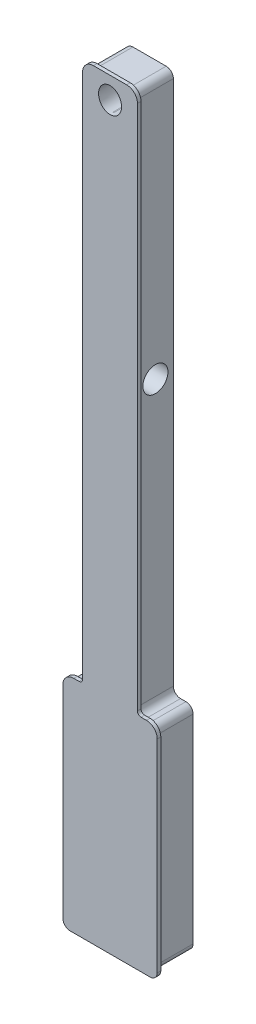
SolidWorks part; units mm, degrees
ref_plane "Plan de face" through (0, 0, 0) normal (0, 0, 1) x (1, 0, 0)
ref_plane "Plan de dessus" through (0, 0, 0) normal (0, 1, 0) x (1, 0, 0)
ref_plane "Plan de droite" through (0, 0, 0) normal (1, 0, 0) x (0, 0, -1)
sketch "Esquisse1" plane through (0, 0, 0) normal (0, 0, 1) x (1, 0, 0)
  line L5 (-28.748, 301.5704) -> (-28.748, 373.5704)
  line L12 (-34.248, 163.5704) -> (-9.978, 163.5704)
  line L21 (-34.248, 223.0046) -> (-28.748, 223.0046)
  line L22 (-34.248, 163.5704) -> (-34.248, 223.0046)
  line L28 (-15.478, 301.5704) -> (-15.478, 223.5671)
  line L29 (-15.478, 223.5671) -> (-15.478, 223.0046)
  line L30 (-15.478, 223.0046) -> (-9.978, 223.0046)
  line L31 (-9.978, 223.0046) -> (-9.978, 163.5704)
  line L36 (-28.748, 223.0046) -> (-28.748, 301.5704)
  line L38 (-28.748, 373.5704) -> (-15.478, 373.5704)
  line L39 (-15.478, 373.5704) -> (-15.478, 301.5704)
  dimension "D2" = 5.5
  dimension "D3" = 5.5
  dimension "D11" = 24.27
extrude "Boss.-Extru.1" add sketch "Esquisse1" along normal blind 10 contours L31 L12 L22 L21 L36 L5 L38 L39 L28 L29 L30
sketch "Esquisse2" plane through (0, 0, 10) normal (0, 0, 1) x (1, 0, 0)
  line L0 (-22.113, 373.5704) -> (-22.113, 368.5704) construction
  line L1 (-28.748, 373.5704) -> (-15.478, 373.5704) construction
  line L2 (-28.748, 223.0046) -> (-28.748, 373.5704) construction
  ellipse E0 centre (-22.113, 368.5704) end of major axis (-22.113, 372.0704) minor radius 3
  dimension "D1" = 6.635
  dimension "D2" = 5
extrude "Enlèv. mat.-Extru.1" cut sketch "Esquisse2" against normal blind 10
sketch "Esquisse3" plane through (0, 0, 10) normal (0, 0, 1) x (1, 0, 0)
  circle A0 centre (-22.113, 368.5704) radius 3.2
extrude "Enlèv. mat.-Extru.2" cut sketch "Esquisse3" against normal blind 10
sketch "Esquisse4" plane through (-15.478, 0, 0) normal (1, 0, 0) x (0, 0, -1)
  line L0 (-5, 373.5704) -> (-5, 301.5704) construction
  line L1 (-10, 373.5704) -> (0, 373.5704) construction
  circle A0 centre (-5, 301.5704) radius 3.5
extrude "Enlèv. mat.-Extru.3" cut sketch "Esquisse4" against normal blind 30 contours A0
sketch "Esquisse5" plane through (0, 0, 10) normal (0, 0, 1) x (1, 0, 0)
  line L0 (-9.978, 223.0046) -> (-9.978, 163.5704) construction
  line L1 (-35.248, 374.5704) -> (-8.978, 374.5704)
  line L2 (-35.248, 374.5704) -> (-35.248, 162.5704)
  line L3 (-35.248, 162.5704) -> (-8.978, 162.5704)
  line L4 (-8.978, 374.5704) -> (-8.978, 162.5704)
  line L5 (-34.248, 163.5704) -> (-34.248, 223.0046) construction
  line L6 (-34.248, 163.5704) -> (-9.978, 163.5704) construction
  line L7 (-28.748, 373.5704) -> (-15.478, 373.5704) construction
  dimension "D1" = 1
  dimension "D2" = 1
  dimension "D3" = 1
  dimension "D4" = 1
extrude "Boss.-Extru.2" add sketch "Esquisse5" along normal blind 1 contours L2 L3 L4 L1
fillet "Congé1" radius 2 8 edges at (-15.478, 223.0046, 5) (-28.748, 223.0046, 5) (-9.978, 163.5704, 5) (-34.248, 163.5704, 5) (-28.748, 373.5704, 5) (-34.248, 223.0046, 5) (-9.978, 223.0046, 5) (-15.478, 373.5704, 5)
sketch "Esquisse6" plane through (0, 0, 10) normal (0, 0, -1) x (-1, 0, 0)
  line L0 (10.5638, 222.4188) -> (10.6442, 223.1259) construction
  line L1 (9.978, 221.0046) -> (8.978, 221.0046) construction
  line L3 (11.978, 223.0046) -> (11.978, 224.0046) construction
  line L4 (15.478, 225.0046) -> (14.478, 225.0046) construction
  line L5 (14.8922, 223.5904) -> (14.6071, 223.8732) construction
  line L6 (22.113, 374.5704) -> (22.113, 127.1098) construction
  line L7 (35.248, 374.5704) -> (8.978, 374.5704) construction
  line L8 (28.748, 225.0046) -> (29.748, 225.0046) construction
  line L9 (29.3338, 223.5904) -> (29.6188, 223.8732) construction
  line L10 (32.248, 223.0046) -> (32.248, 224.0046) construction
  line L11 (33.6622, 222.4188) -> (33.5818, 223.1259) construction
  line L12 (34.248, 221.0046) -> (35.248, 221.0046) construction
  line L13 (13.478, 223.0046) -> (13.478, 224.0046) construction
  line L14 (11.978, 224.0046) -> (13.478, 224.0046)
  line L15 (32.248, 224.0046) -> (30.748, 224.0046)
  line L16 (15.478, 371.5704) -> (14.478, 371.5704) construction
  line L17 (16.0638, 372.9847) -> (15.3098, 373.6441) construction
  line L18 (17.478, 373.5704) -> (17.478, 374.5704) construction
  line L20 (14.478, 371.5704) -> (14.478, 225.0046)
  line L23 (17.478, 374.5704) -> (17.478, 374.9841)
  line L24 (35.248, 221.0046) -> (36.748, 374.5705)
  line L25 (32.248, 224.0046) -> (30.748, 224.0046)
  line L26 (29.748, 371.5704) -> (29.748, 225.0046)
  line L27 (9.978, 221.0046) -> (9.978, 165.5704) construction
  line L29 (17.478, 374.9841) -> (8.9656, 374.9841)
  line L30 (8.9656, 374.9841) -> (8.9656, 221.0046)
  line L31 (9.978, 165.5704) -> (10.3655, 165.5704) construction
  line L32 (10.5638, 164.1562) -> (11.0684, 163.8734) construction
  line L33 (11.978, 163.5704) -> (11.978, 163.1704) construction
  line L35 (32.248, 163.5704) -> (11.978, 163.5704) construction
  line L43 (8.9656, 221.0046) -> (8.978, 221.0046)
  line L44 (32.248, 224.0046) -> (30.748, 224.0046)
  line L45 (29.748, 371.5704) -> (29.748, 225.0046)
  line L46 (33.6622, 222.4188) -> (34.3693, 223.1259) construction
  line L47 (29.3338, 223.5904) -> (30.0409, 224.2975) construction
  line L48 (26.748, 374.5704) -> (36.748, 374.5705)
  arc A0 (11.978, 223.0046) -> (9.978, 221.0046) centre (11.978, 221.0046) ccw construction
  arc A1 (11.978, 224.0046) -> (8.978, 221.0046) centre (11.978, 221.0046) ccw
  arc A2 (13.478, 223.0046) -> (15.478, 225.0046) centre (13.478, 225.0046) ccw construction
  arc A4 (13.478, 224.0046) -> (14.478, 225.0046) centre (13.478, 225.0046) ccw
  arc A5 (30.748, 224.0046) -> (29.748, 225.0046) centre (30.748, 225.0046) cw
  arc A7 (17.478, 373.5704) -> (15.478, 371.5704) centre (17.478, 371.5704) ccw construction
  arc A10 (30.748, 224.0046) -> (29.748, 225.0046) centre (30.748, 225.0046) cw
  arc A11 (29.748, 371.5704) -> (26.748, 374.5704) centre (26.6739, 371.4963) ccw
  arc A12 (14.478, 371.5704) -> (17.478, 374.5704) centre (17.478, 371.5704) cw
  arc A13 (9.978, 165.5704) -> (11.978, 163.5704) centre (11.978, 165.5704) ccw construction
  arc A16 (32.248, 224.0046) -> (35.248, 221.0046) centre (32.248, 221.0046) cw
  arc A17 (30.748, 224.0046) -> (29.748, 225.0046) centre (30.748, 225.0046) cw
  arc A18 (29.748, 371.5704) -> (26.748, 374.5704) centre (26.748, 371.5704) ccw
  dimension "D1" = 1
  dimension "D2" = 1
extrude "Enlèv. mat.-Extru.4" cut sketch "Esquisse6" against normal blind 1
fillet "Congé4" radius 2 2 edges at (-35.248, 162.5704, 10.5) (-8.978, 162.5704, 10.5)
sketch "Esquisse10" plane through (0, 0, 0) normal (0, 0, -1) x (-1, 0, 0)
  circle A0 centre (22.113, 368.5704) radius 3.2
extrude "Enlèv. mat.-Extru.9" cut sketch "Esquisse10" against normal blind 15 contours A0
sketch "Esquisse11" plane through (0, 0, 0) normal (0, 0, -1) x (-1, 0, 0)
  arc A0 (24.4723, 366.4085) -> (24.4723, 370.7324) centre (22.113, 368.5704) ccw construction
  ellipse E0 centre (22.113, 368.5704) end of major axis (22.1713, 372.0698) minor radius 3.2
extrude "Enlèv. mat.-Extru.10" cut sketch "Esquisse11" against normal blind 15 contours E0
